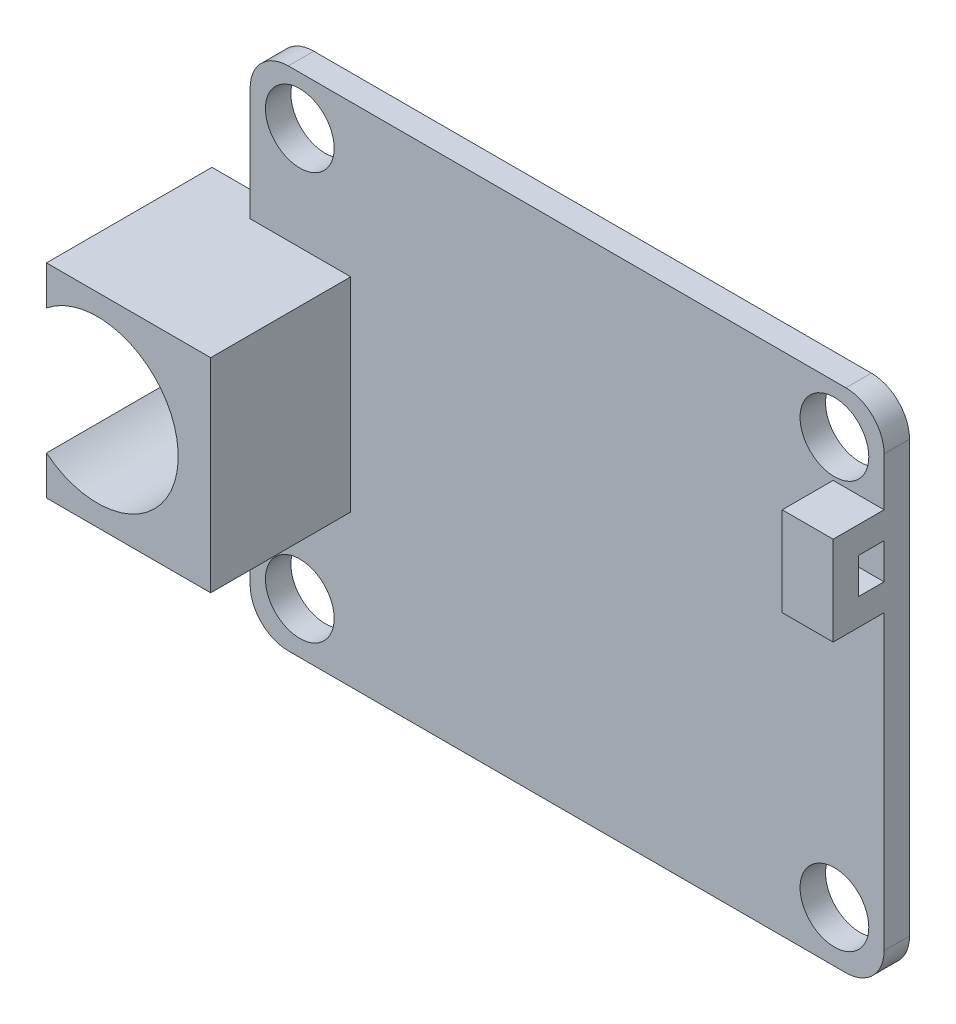
SolidWorks part; units mm, degrees
ref_plane "Alzado" through (0, 0, 0) normal (0, 0, 1) x (1, 0, 0)
ref_plane "Planta" through (0, 0, 0) normal (0, 1, 0) x (1, 0, 0)
ref_plane "Vista lateral" through (0, 0, 0) normal (1, 0, 0) x (0, 0, -1)
sketch "Croquis1" plane through (0, 0, 0) normal (0, 0, 1) x (1, 0, 0)
  line L1 (-56.8634, 16.1421) -> (-7.0634, 16.1421)
  line L2 (-56.8634, 16.1421) -> (-56.8634, -23.6579)
  line L3 (-56.8634, -23.6579) -> (-7.0634, -23.6579)
  line L4 (-7.0634, 16.1421) -> (-7.0634, -23.6579)
  circle A0 centre (-52.9634, 12.3421) radius 2.7
  circle A1 centre (-10.9634, 12.3421) radius 2.7
  circle A2 centre (-10.9634, -19.6579) radius 2.7
  circle A3 centre (-52.9634, -19.6579) radius 2.7
  dimension "D3" = 3.8
  dimension "D7" = 5.4
  dimension "D1" = 49.8
  dimension "D2" = 39.8
  dimension "D4" = 3.9
  dimension "D5" = 2
  dimension "D6" = 2
extrude "Saliente-Extruir1" add sketch "Croquis1" along normal blind 6
sketch "Croquis2" plane through (0, 0, 6) normal (0, 0, 1) x (1, 0, 0)
  line L0 (-56.8634, -23.6579) -> (-7.0634, 16.1421) construction
  line L2 (-49.9634, -16.7579) -> (-13.9634, -16.7579)
  line L3 (-51.9634, -14.7579) -> (-51.9634, 7.2421)
  line L4 (-49.9634, 9.2421) -> (-13.9634, 9.2421)
  line L5 (-11.9634, -14.7579) -> (-11.9634, 7.2421)
  line L6 (-51.9634, -16.7579) -> (-11.9634, 9.2421) construction
  line L7 (-51.9634, 9.2421) -> (-11.9634, -16.7579) construction
  arc A0 (-11.9634, 7.2421) -> (-13.9634, 9.2421) centre (-13.9634, 7.2421) ccw
  arc A1 (-11.9634, -14.7579) -> (-13.9634, -16.7579) centre (-13.9634, -14.7579) cw
  arc A2 (-49.9634, -16.7579) -> (-51.9634, -14.7579) centre (-49.9634, -14.7579) cw
  arc A3 (-49.9634, 9.2421) -> (-51.9634, 7.2421) centre (-49.9634, 7.2421) ccw
  point P4 (-31.9634, -3.7579)
  dimension "D3" = 2
  dimension "D1" = 40
  dimension "D2" = 26
extrude "Cortar-Extruir1" cut sketch "Croquis2" against normal blind 4
fillet "Redondeo1" radius 3 4 edges at (-56.8634, 16.1421, 3) (-7.0634, 16.1421, 3) (-7.0634, -23.6579, 3) (-56.8634, -23.6579, 3)
sketch "Croquis4" plane through (0, 0, 0) normal (0, 0, -1) x (-1, 0, 0)
  line L1 (56.8634, 13.1421) -> (56.8634, -20.6579) construction
  line L2 (56.8634, 4.2421) -> (61.8634, 4.2421)
  line L4 (61.8634, -11.7579) -> (56.8634, -11.7579)
  line L6 (56.8634, 4.2421) -> (61.8634, -11.7579) construction
  line L7 (57.8634, -0.2579) -> (61.8634, -0.2579)
  line L8 (57.8634, -7.2579) -> (61.8634, -7.2579)
  line L9 (61.8634, 4.2421) -> (61.8634, -0.2579)
  line L10 (61.8634, -7.2579) -> (61.8634, -11.7579)
  line L11 (56.8634, 4.2421) -> (56.8634, -0.4038)
  line L12 (56.8634, -7.112) -> (56.8634, -11.7579)
  arc A2 (57.8634, -0.2579) -> (56.8634, -0.4038) centre (57.8634, -3.7579) ccw
  arc A3 (57.8634, -7.2579) -> (56.8634, -7.112) centre (57.8634, -3.7579) cw
  dimension "D1" = 5
  dimension "D2" = 3.5
  dimension "D3" = 5
extrude "Saliente-Extruir3" add sketch "Croquis4" against normal blind 3
sketch "Croquis5" plane through (0, 0, 3) normal (0, 0, 1) x (1, 0, 0)
  circle A1 centre (-57.8634, -3.7579) radius 6.35
extrude "Cortar-Extruir2" cut sketch "Croquis5" along normal up to vertex (3 mm away)
sketch "Croquis6" plane through (0, 0, 3) normal (0, 0, 1) x (1, 0, 0)
  line L6 (-61.8634, 4.2421) -> (-51.9634, 4.2421)
  line L8 (-51.9634, -11.7579) -> (-61.8634, -11.7579)
  line L9 (-61.8634, 4.2421) -> (-61.8634, 1.1739)
  line L10 (-61.8634, -0.2579) -> (-61.8634, 4.2421) construction
  line L11 (-61.8634, -11.7579) -> (-61.8634, -8.6897)
  line L12 (-51.9634, 4.2421) -> (-48.9634, 4.2421)
  line L13 (-48.9634, 4.2421) -> (-48.9634, -11.7579)
  line L14 (-48.9634, -11.7579) -> (-51.9634, -11.7579)
  arc A5 (-61.8634, 1.1739) -> (-61.8634, -8.6897) centre (-57.8634, -3.7579) cw
extrude "Saliente-Extruir4" add sketch "Croquis6" along normal blind 10
sketch "Croquis7" plane through (0, 0, 2) normal (0, 0, 1) x (1, 0, 0)
  line L0 (-51.9634, -3.7579) -> (-51.9634, 4.2421)
  line L1 (-51.9634, 7.2421) -> (-51.9634, -14.7579) construction
  line L2 (-51.9634, 4.2421) -> (-48.9634, 4.2421)
  line L3 (-48.9634, 4.2421) -> (-48.9634, -11.7579)
  line L4 (-48.9634, -11.7579) -> (-51.9634, -11.7579)
  line L5 (-51.9634, -11.7579) -> (-51.9634, -3.7579)
extrude "Saliente-Extruir5" add sketch "Croquis7" along normal blind 2
sketch "Croquis8" plane through (0, 0, 3) normal (0, 0, 1) x (1, 0, 0)
  line L0 (-56.8634, -0.4038) -> (-56.8634, -7.112)
  arc A0 (-56.8634, -0.4038) -> (-56.8634, -7.112) centre (-56.8634, -3.7579) cw
extrude "Cortar-Extruir3" cut sketch "Croquis8" against normal up to vertex
sketch "Croquis9" plane through (0, 0, 6) normal (0, 0, 1) x (1, 0, 0)
  line L0 (-56.8634, -11.7579) -> (-56.8634, -27.4922)
  line L1 (-56.8634, -27.4922) -> (-1.8171, -27.4922)
  line L2 (-1.8171, -27.4922) -> (-1.8171, 22.8618)
  line L3 (-1.8171, 22.8618) -> (-56.8634, 22.8618)
  line L4 (-56.8634, 22.8618) -> (-56.8634, 4.2421)
  line L5 (-56.8634, 4.2421) -> (-47.1727, 4.2421)
  line L6 (-47.1727, 4.2421) -> (-47.1727, -11.7579)
  line L7 (-47.1727, -11.7579) -> (-56.8634, -11.7579)
extrude "Cortar-Extruir4" cut sketch "Croquis9" against normal blind 4
sketch "Croquis10" plane through (0, 0, 2) normal (0, 0, 1) x (1, 0, 0)
  line L0 (-7.0634, -20.6579) -> (-7.0634, 13.1421) construction
  line L1 (-7.0634, 9.3421) -> (-11.0634, 9.3421)
  line L2 (-7.0634, 9.3421) -> (-7.0634, 2.3421)
  line L3 (-7.0634, 2.3421) -> (-11.0634, 2.3421)
  line L4 (-11.0634, 9.3421) -> (-11.0634, 2.3421)
  circle A0 centre (-10.9634, 12.3421) radius 2.7 construction
  point P6 (-9.0634, 9.3421)
  dimension "D1" = 7
  dimension "D2" = 3
  dimension "D3" = 4
extrude "Saliente-Extruir6" add sketch "Croquis10" along normal blind 4
sketch "Croquis11" plane through (-7.0634, 0, 0) normal (1, 0, 0) x (0, 0, -1)
  line L0 (-6, 5.8421) -> (-2, 5.8421) construction
  line L1 (-6, 2.3421) -> (-6, 9.3421) construction
  line L2 (-2, 5.8421) -> (-2, 7.2421)
  line L3 (-2, 7.2421) -> (-4, 7.2421)
  line L4 (-4, 7.2421) -> (-4, 4.4421)
  line L5 (-4, 4.4421) -> (-2, 4.4421)
  line L6 (-2, 4.4421) -> (-2, 5.8421)
  dimension "D1" = 1.4
  dimension "D2" = 1.4
extrude "Cortar-Extruir5" cut sketch "Croquis11" against normal up to vertex
